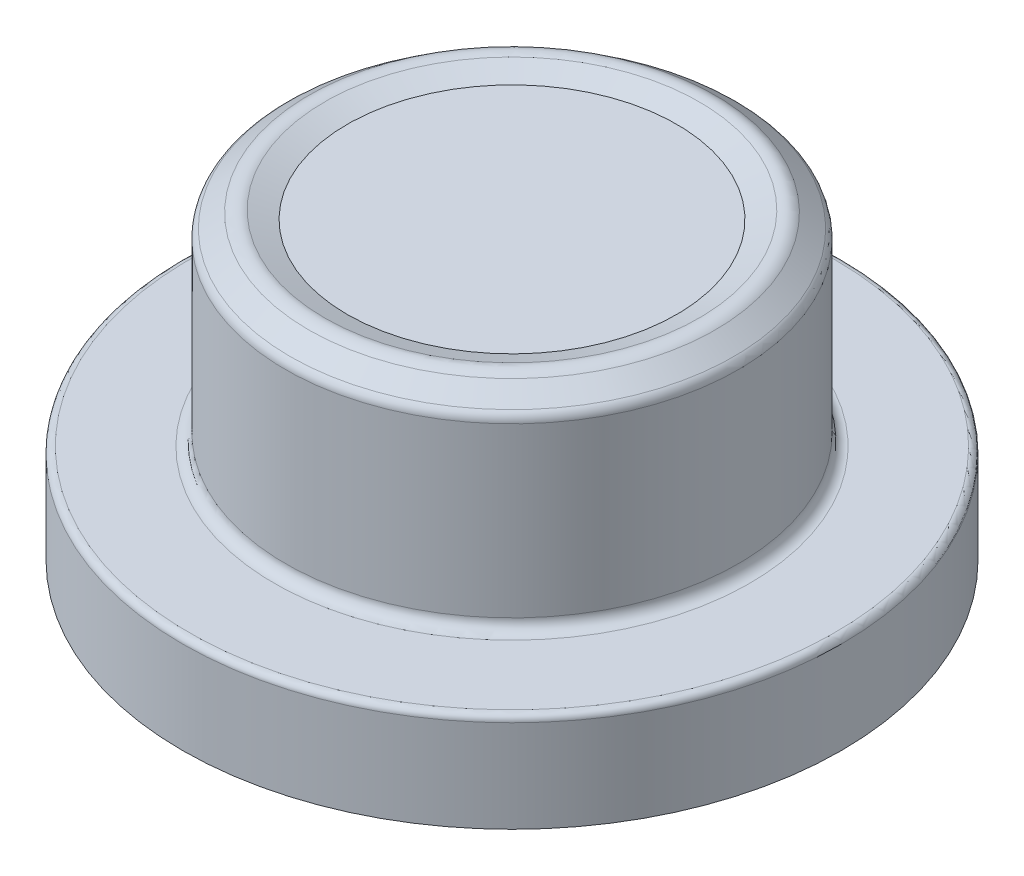
SolidWorks part; units mm, degrees
ref_plane "Front Plane" through (0, 0, 0) normal (0, 0, 1) x (1, 0, 0)
ref_plane "Top Plane" through (0, 0, 0) normal (0, 1, 0) x (1, 0, 0)
ref_plane "Right Plane" through (0, 0, 0) normal (1, 0, 0) x (0, 0, -1)
sketch "Sketch1" plane through (0, 0, 0) normal (1, 0, 0) x (0, 0, -1)
  line L0 (0, 5.9309) -> (0, -5.9309) construction
  line L2 (12.7, -5.8039) -> (12.7, -1.9939)
  line L3 (12.7, -1.9939) -> (8.7249, -1.9939)
  line L4 (8.7249, -1.9939) -> (8.7249, 5.9309)
  line L5 (8.7249, 5.9309) -> (0, 5.9309)
  line L6 (6.35, 5.9309) -> (6.35, 4.3459)
  line L7 (7.5375, -0.0127) -> (0, -0.0127)
  line L8 (6.35, 5.5754) -> (7.2178, 5.8913)
  line L9 (6.35, 4.3459) -> (6.9437, 4.3459) construction
  line L10 (7.5375, 4.3459) -> (7.5375, -0.0127)
  line L12 (6.9437, 4.3459) -> (7.5375, 4.3459) construction
  line L13 (7.5375, 4.3459) -> (8.1312, 4.3459) construction
  line L14 (8.1312, 4.3459) -> (8.7249, 4.3459) construction
  line L15 (7.8343, 5.8011) -> (8.7249, 5.1384)
  line L16 (11.1125, -5.9309) -> (11.1125, -5.6769)
  line L17 (11.1125, -5.6769) -> (0, -5.6769)
  line L18 (11.1125, -5.9309) -> (0, -5.9309)
  line L19 (11.1125, -5.8039) -> (12.7, -5.8039)
  line L25 (2.794, 4.3459) -> (2.921, 4.3459)
  line L26 (2.794, 4.3459) -> (2.794, 4.4729)
  line L27 (2.794, 4.4729) -> (2.921, 4.4729)
  line L28 (2.921, 4.3459) -> (2.921, 4.4729)
  arc A1 (7.2178, 5.8913) -> (7.8343, 5.8011) centre (7.4424, 5.2743) cw
  point P2 (0, 0)
  point P16 (7.5375, 5.924)
  point P21 (7.8343, 4.3459)
  point P29 (6.35, 5.1384)
  point P32 (2.794, 4.4729)
  point P35 (2.921, 4.4729)
  dimension "Overall Height" = 11.8618
  dimension "Base Diameter" = 25.4
  dimension "Diameter" = 17.4498
  dimension "D2" = 20
  dimension "Glass Diameter" = 12.7
  dimension "D1" = 1.9812
  dimension "D4" = 1.585
  dimension "Base Height" = 3.937
  dimension "D5" = 0.254
  dimension "Magnet Diameter" = 22.225
  dimension "D3" = 0.127
  dimension "Centering Circle Diameter" = 5.588
sketch "Sketch3" plane through (0, 0, 0) normal (1, 0, 0) x (0, 0, -1)
  line L0 (6.35, 5.5754) -> (7.2178, 5.8913) construction
  line L1 (6.35, 5.5754) -> (7.2178, 5.8913)
  line L2 (7.5375, 4.3459) -> (7.5375, -0.0127) construction
  line L3 (7.5375, -0.0127) -> (0, -0.0127) construction
  line L4 (12.7, -1.9939) -> (8.7249, -1.9939) construction
  line L6 (12.7, -5.8039) -> (12.7, -1.9939) construction
  line L7 (7.5375, 4.3459) -> (7.5375, -0.0127)
  line L8 (7.5375, -0.0127) -> (0, -0.0127)
  line L9 (12.7, -1.9939) -> (8.7249, -1.9939)
  line L11 (12.7, -5.8039) -> (12.7, -1.9939)
  line L12 (6.35, 5.5754) -> (6.35, 4.3459)
  line L13 (6.35, 4.3459) -> (7.5375, 4.3459)
  line L15 (8.7249, 5.1384) -> (8.7249, -1.9939)
  line L19 (7.8343, 5.8011) -> (8.7249, 5.1384) construction
  line L20 (7.8343, 5.8011) -> (8.7249, 5.1384)
  line L21 (0, -0.0127) -> (0, -5.6769)
  line L22 (0, -5.6769) -> (11.1125, -5.6769)
  line L23 (11.1125, -5.6769) -> (11.1125, -5.8039)
  line L24 (11.1125, -5.8039) -> (12.7, -5.8039)
  arc A2 (7.8343, 5.8011) -> (7.2178, 5.8913) centre (7.4424, 5.2743) ccw construction
  arc A3 (7.8343, 5.8011) -> (7.2178, 5.8913) centre (7.4424, 5.2743) ccw
revolve "Revolve1" add sketch "Sketch3" angle 360 about L21
sketch "Sketch4" plane through (0, 0, 0) normal (1, 0, 0) x (0, 0, -1)
  line L0 (0, 5.9309) -> (0, -5.9309) construction
  line L1 (6.35, 5.5754) -> (0, 5.5754)
  line L2 (6.35, 5.5754) -> (6.35, 4.3459)
  line L3 (6.35, 4.3459) -> (2.921, 4.3459)
  line L4 (0, 5.5754) -> (0, 4.3459)
  line L5 (2.921, 4.3459) -> (2.921, 4.4729) construction
  line L6 (2.794, 4.4729) -> (2.921, 4.4729) construction
  line L7 (2.794, 4.3459) -> (2.794, 4.4729) construction
  line L8 (2.921, 4.3459) -> (2.921, 4.4729)
  line L9 (2.794, 4.4729) -> (2.921, 4.4729)
  line L10 (2.794, 4.3459) -> (2.794, 4.4729)
  line L11 (2.794, 4.3459) -> (0, 4.3459)
revolve "Revolve2" add sketch "Sketch4" angle 360 about L4
sketch "Sketch5" plane through (0, 0, 0) normal (1, 0, 0) x (0, 0, -1)
  line L0 (2.921, 4.3459) -> (2.921, 4.4729) construction
  line L1 (0, -5.9309) -> (11.1125, -5.9309)
  line L2 (0, -5.9309) -> (0, -5.6769)
  line L3 (0, -5.6769) -> (11.1125, -5.6769)
  line L4 (11.1125, -5.9309) -> (11.1125, -5.6769)
  line L9 (2.794, 4.3459) -> (2.794, 4.4729) construction
  line L10 (2.794, 4.4729) -> (2.921, 4.4729) construction
  line L11 (2.921, 4.3459) -> (2.921, 4.4729)
  line L12 (2.794, 4.3459) -> (2.794, 4.4729)
  line L13 (2.794, 4.4729) -> (2.921, 4.4729)
  line L14 (2.794, 4.3459) -> (2.921, 4.3459)
revolve "Revolve3" add sketch "Sketch5" angle 360 about L2
fillet "Fillet1" radius 0.4362 2 edges at (0, -1.9939, 8.7249) (0, 5.1384, 8.7249)
fillet "Fillet2" radius 0.254 1 edges at (0, -1.9939, 12.7)
equation "\"D4@Sketch1\"=0.2*(\"Overall Height@Sketch1\"-\"Base Height@Sketch1\")"
equation "\"D1@Fillet1\"=.025*\"Diameter@Sketch1\""
equation "\"D1@Fillet2\"=.01*\"Base Diameter@Sketch1\""
equation "\"D1@Sketch1\"=(\"Overall Height@Sketch1\"-\"Base Height@Sketch1\")*0.25"
equation "\"Magnet Diameter@Sketch1\"=\"Base Diameter@Sketch1\"-.125"
